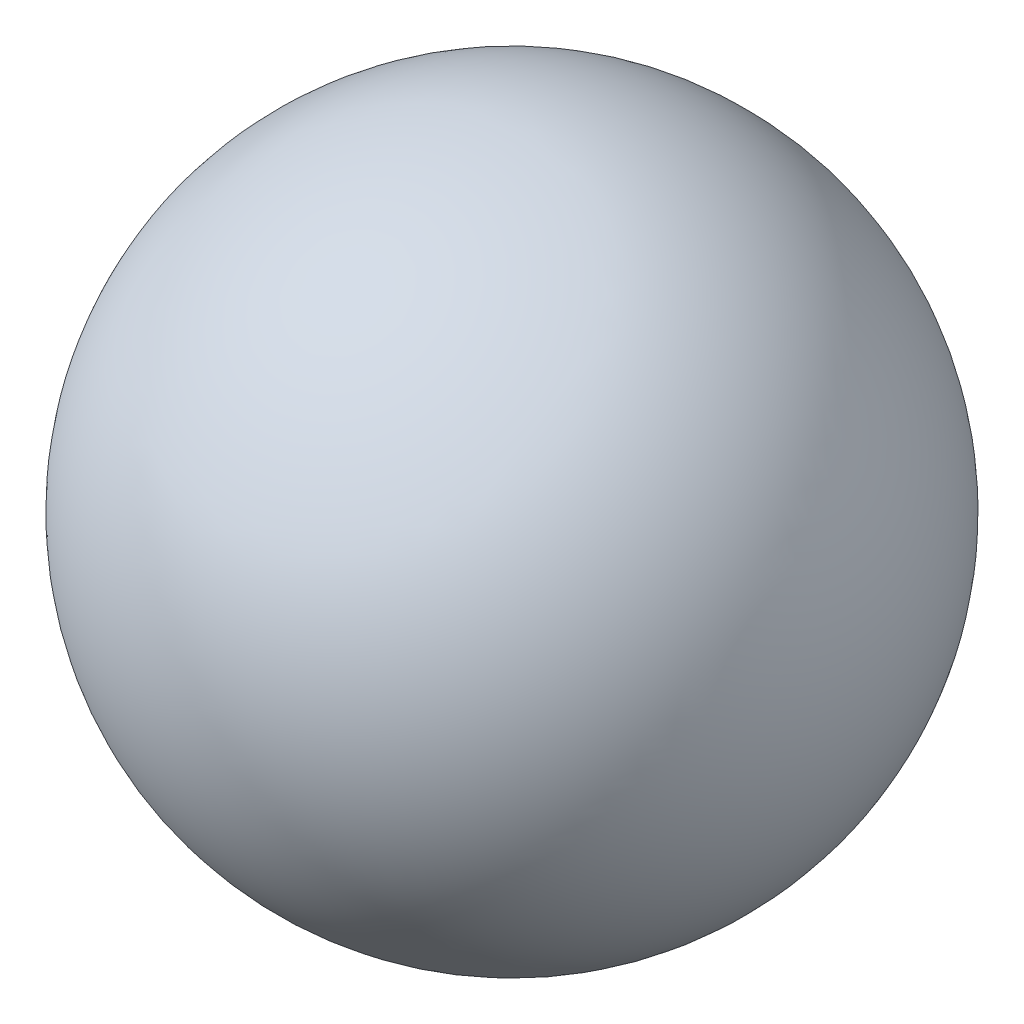
SolidWorks part; units mm, degrees
ref_plane "Front Plane" through (0, 0, 0) normal (0, 0, 1) x (1, 0, 0)
ref_plane "Top Plane" through (0, 0, 0) normal (0, 1, 0) x (1, 0, 0)
ref_plane "Right Plane" through (0, 0, 0) normal (1, 0, 0) x (0, 0, -1)
sketch "Sketch1" plane through (0, 0, 0) normal (0, 0, 1) x (1, 0, 0)
  line L0 (-7.5, 0) -> (7.5, 0)
  arc A0 (7.5, 0) -> (-7.5, 0) centre (0, 0) ccw
  dimension "D1" = 15
revolve "Revolve1" add sketch "Sketch1" angle 360 about L0
scale "Scale1" scale about centroid uniform scaling yes scale factor 1.9329
scale "Scale2" scale about centroid uniform scaling yes scale factor 1.5
